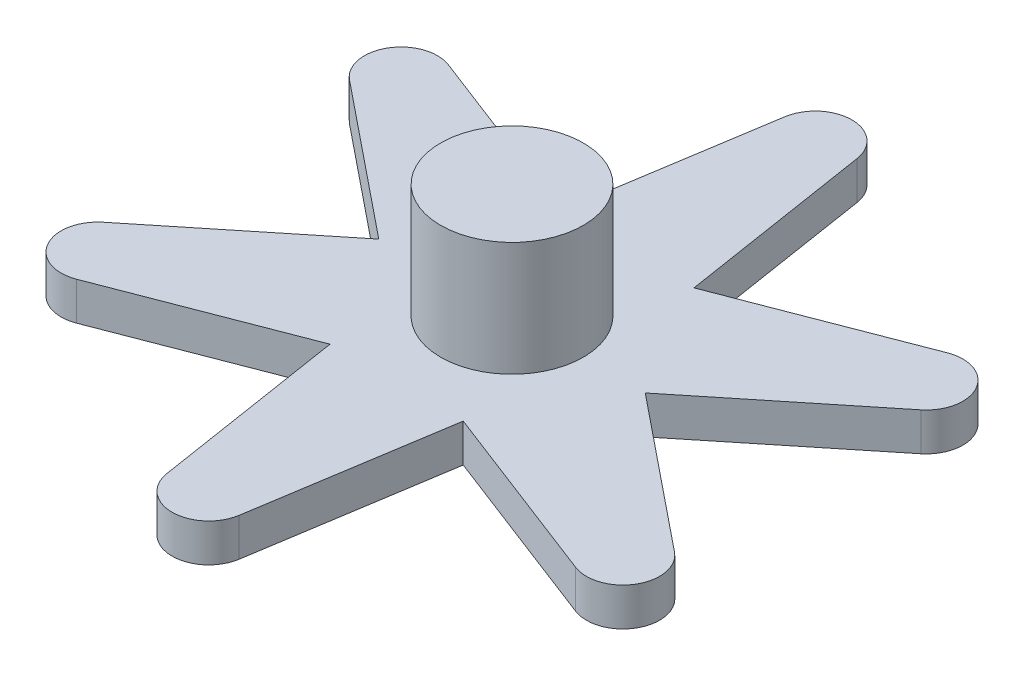
SolidWorks part; units mm, degrees
ref_plane "Front Plane" through (0, 0, 0) normal (0, 0, 1) x (1, 0, 0)
ref_plane "Top Plane" through (0, 0, 0) normal (0, 1, 0) x (1, 0, 0)
ref_plane "Right Plane" through (0, 0, 0) normal (1, 0, 0) x (0, 0, -1)
sketch "Sketch1" plane through (0, 0, 0) normal (0, 1, 0) x (1, 0, 0)
  circle A0 centre (0, 0) radius 7
  dimension "D1" = 14
extrude "Boss-Extrude1" add sketch "Sketch1" along normal blind 2
sketch "Sketch2" plane through (0, 2, 0) normal (0, 1, 0) x (1, 0, 0)
  line L0 (0, 0) -> (0, 15.9335) construction
  line L1 (-3.5, 6.0622) -> (-1.9, 16.2324)
  line L2 (1.9, 16.2324) -> (3.5, 6.0622)
  arc A0 (-1.9, 16.2324) -> (1.9, 16.2324) centre (0, 15.9335) cw
  circle A1 centre (0, 0) radius 7 construction
  arc A2 (-3.5, 6.0622) -> (3.5, 6.0622) centre (0, 0) cw
  dimension "D1" = 7
  dimension "D2" = 3.8
extrude "Boss-Extrude2" add sketch "Sketch2" against normal up to surface (2 mm away) up to face at (0, 0, 7)
pattern_circular "CirPattern1" count 6 over 360 about axis through (0, 0, 0) along (0, 1, 0) of "Boss-Extrude2"
sketch "Sketch3" plane through (0, 2, 0) normal (0, 1, 0) x (1, 0, 0)
  circle A0 centre (0, 0) radius 3.75
  dimension "D1" = 7.5
extrude "Boss-Extrude3" add sketch "Sketch3" along normal blind 6
